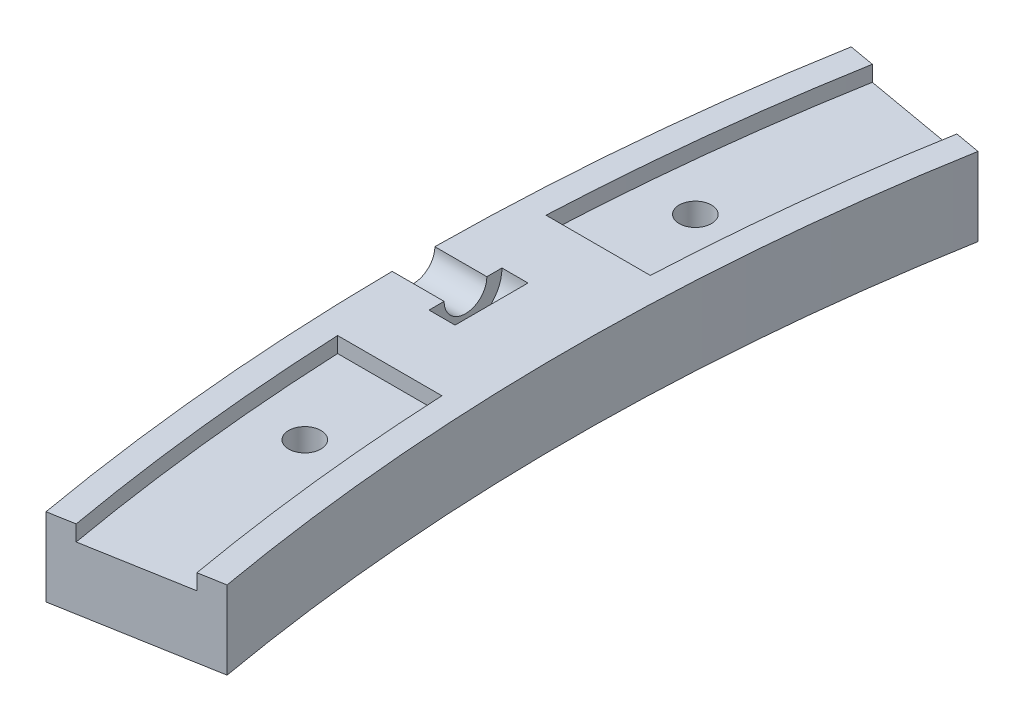
SolidWorks part; units mm, degrees
ref_plane "Front Plane" through (0, 0, 0) normal (0, 0, 1) x (1, 0, 0)
ref_plane "Top Plane" through (0, 0, 0) normal (0, 1, 0) x (1, 0, 0)
ref_plane "Right Plane" through (0, 0, 0) normal (1, 0, 0) x (0, 0, -1)
sketch "Sketch1" plane through (0, 0, 0) normal (0, 1, 0) x (1, 0, 0)
  line L0 (0, 0) -> (-219.1197, -38.6367) construction
  line L1 (0, 0) -> (-219.1197, 38.6367) construction
  line L2 (0, 0) -> (-215, 0) construction
  line L3 (-219.1197, 38.6367) -> (-204.3476, 36.032)
  line L4 (-204.3476, -36.032) -> (-219.1197, -38.6367)
  arc A0 (-216.6577, 38.2026) -> (-216.6577, -38.2026) centre (0, 0) ccw construction
  arc A1 (-206.8096, 36.4661) -> (-206.8096, -36.4661) centre (0, 0) ccw construction
  arc A2 (-211.7337, -37.3344) -> (-211.7337, 37.3344) centre (0, 0) cw construction
  arc A3 (-219.1197, 38.6367) -> (-219.1197, -38.6367) centre (0, 0) ccw
  arc A4 (-204.3476, 36.032) -> (-204.3476, -36.032) centre (0, 0) ccw
  dimension "D1" = 220
  dimension "D2" = 210
  dimension "D3" = 5
  dimension "D5" = 2.5
  dimension "D6" = 2.5
  dimension "D4" = 20
extrude "Boss-Extrude1" add sketch "Sketch1" along normal blind 7.5
sketch "Sketch2" plane through (0, 7.5, 0) normal (0, 1, 0) x (1, 0, 0)
  line L2 (0, 0) -> (-215, 0) construction
  line L3 (0, 0) -> (-219.1197, -38.6367) construction
  line L4 (0, 0) -> (-219.1197, 38.6367) construction
  line L5 (0, 0) -> (-210, 0) construction
  line L6 (0, 0) -> (-219.1197, -38.6367) construction
  line L7 (0, 0) -> (-219.1197, 38.6367) construction
  line L8 (0, 10) -> (-222.2752, 10) construction
  line L9 (0, 10) -> (0, -10) construction
  line L10 (0, -10) -> (-222.2752, -10) construction
  line L11 (-216.6577, 38.2026) -> (-206.8096, 36.4661)
  line L12 (-216.6577, -38.2026) -> (-206.8096, -36.4661)
  line L13 (-219.7726, -10) -> (-209.7618, -10)
  line L14 (-209.7618, 10) -> (-219.7726, 10)
  arc A0 (-216.6577, 38.2026) -> (-216.6577, -38.2026) centre (0, 0) ccw construction
  arc A1 (-206.8096, 36.4661) -> (-206.8096, -36.4661) centre (0, 0) ccw construction
  arc A2 (-216.6577, 38.2026) -> (-216.6577, -38.2026) centre (0, 0) ccw
  arc A3 (-206.8096, 36.4661) -> (-206.8096, -36.4661) centre (0, 0) ccw
  arc A4 (-219.1197, 38.6367) -> (-219.1197, -38.6367) centre (0, 0) ccw construction
  line M2 (-219.1197, -38.6367) -> (-204.3476, -36.032)
  line M4 (-204.3476, 36.032) -> (-219.1197, 38.6367)
  dimension "D1" = 20
extrude "Cut-Extrude1" cut sketch "Sketch2" against normal blind 1.5 contours A3 A2 L14 M4 | A3 L13 A2 M2
ref_plane "Plane1" through (-215, 0, 0) normal (1, 0, 0) x (0, 0, -1)
sketch "Sketch4" plane through (-215, 0, 0) normal (1, 0, 0) x (0, 0, -1)
  line L0 (36.032, 7.5) -> (-36.032, 7.5) construction
  circle A0 centre (0, 7.5) radius 3.5
  dimension "D1" = 7
extrude "Cut-Extrude3" cut sketch "Sketch4" against normal blind 2.5
sketch "Sketch5" plane through (-215, 0, 0) normal (1, 0, 0) x (0, 0, -1)
  line L0 (36.032, 7.5) -> (-36.032, 7.5) construction
  circle A0 centre (0, 7.5) radius 2.05
  dimension "D1" = 4.1
extrude "Cut-Extrude4" cut sketch "Sketch5" against normal through all
sketch "Sketch6" plane through (0, 0, 0) normal (0, -1, 0) x (1, 0, 0)
  line L0 (0, 0) -> (-214.1819, 18.7385) construction
  line L1 (0, 0) -> (-215, 0) construction
  line L2 (0, 0) -> (-215, 0) construction
  line L3 (0, 0) -> (-214.1819, -18.7385) construction
  arc A0 (-211.7337, 37.3344) -> (-211.7337, -37.3344) centre (0, 0) ccw construction
  dimension "D1" = 5
hole_wizard "Ø3.1 (3.1) Diameter Hole1" positions "Sketch7" profile "Sketch8" hole size "Ø3.1" standard "ISO" end condition through all
sketch "Sketch7" plane through (0, 0, 0) normal (0, -1, 0) x (-1, 0, 0)
  point P0 (214.1819, -18.7385)
  point P3 (214.1819, 18.7385)
sketch "Sketch8" plane through (-214.1819, 0, 18.7385) normal (1, 0, 0) x (0, 0, -1)
  line L0 (0, 0) -> (0, 7.6156)
  line L1 (0, 7.6156) -> (1.55, 7.6156)
  line L2 (1.55, 7.6156) -> (1.55, 0)
  line L5 (1.55, 0) -> (0, 0)
  line L11 (0, -6.35) -> (0, 107.95) construction
  dimension "Thru Hole Dia." = 3.1
  dimension "Thru Hole Depth" = 7.6156
